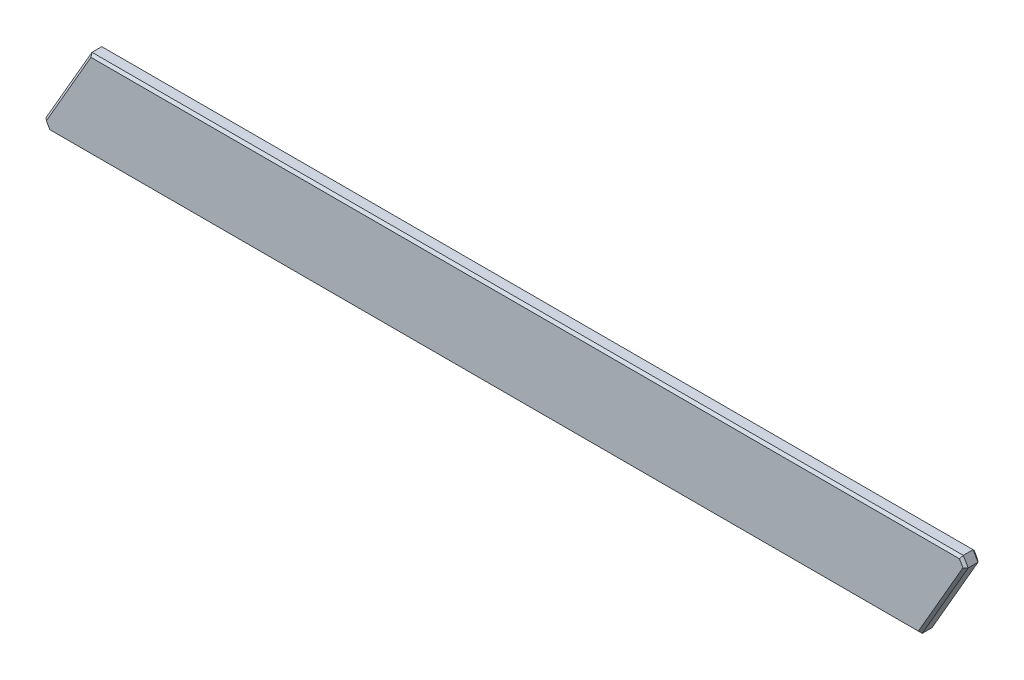
SolidWorks part; units mm, degrees
material "Thornel Mat VMA"
ref_plane "前视基准面" through (0, 0, 0) normal (0, 0, 1) x (1, 0, 0)
ref_plane "上视基准面" through (0, 0, 0) normal (0, 1, 0) x (1, 0, 0)
ref_plane "右视基准面" through (0, 0, 0) normal (1, 0, 0) x (0, 0, -1)
other "Configuration Table"
sketch "草图1" plane through (0, 0, 0) normal (0, 0, 1) x (1, 0, 0)
  line L0 (-111.4216, 0) -> (114.7203, 0) construction
  line L1 (0, -67.6046) -> (0, 58.8992) construction
  line L2 (84.8038, -9) -> (-93.1962, -9)
  line L3 (-94.1962, -7.2679) -> (-84.8038, 9)
  line L4 (-84.8038, 9) -> (93.1962, 9)
  line L5 (94.1962, 7.2679) -> (84.8038, -9)
  line L6 (93.1962, 9) -> (94.1962, 7.2679)
  line L7 (-93.1962, -9) -> (-94.1962, -7.2679)
  point P6 (-95.1962, -9)
  point P9 (95.1962, 9)
  point P13 (90, 0)
  dimension "D1" = 60
  dimension "D2" = 9
  dimension "D3" = 9
  dimension "D4" = 180
  dimension "D5" = 90
extrude "凸台-拉伸1" add sketch "草图1" along normal blind 3
chamfer "倒角1" distance 0.5 angle 45 12 edges at (93.6962, 8.134, 0) (4.1962, 9, 0) (-89.5, 0.866, 0) (-93.6962, -8.134, 0) (-4.1962, -9, 0) (89.5, -0.866, 0) (-4.1962, -9, 3) (-93.6962, -8.134, 3) (-89.5, 0.866, 3) (4.1962, 9, 3) (93.6962, 8.134, 3) (89.5, -0.866, 3)
